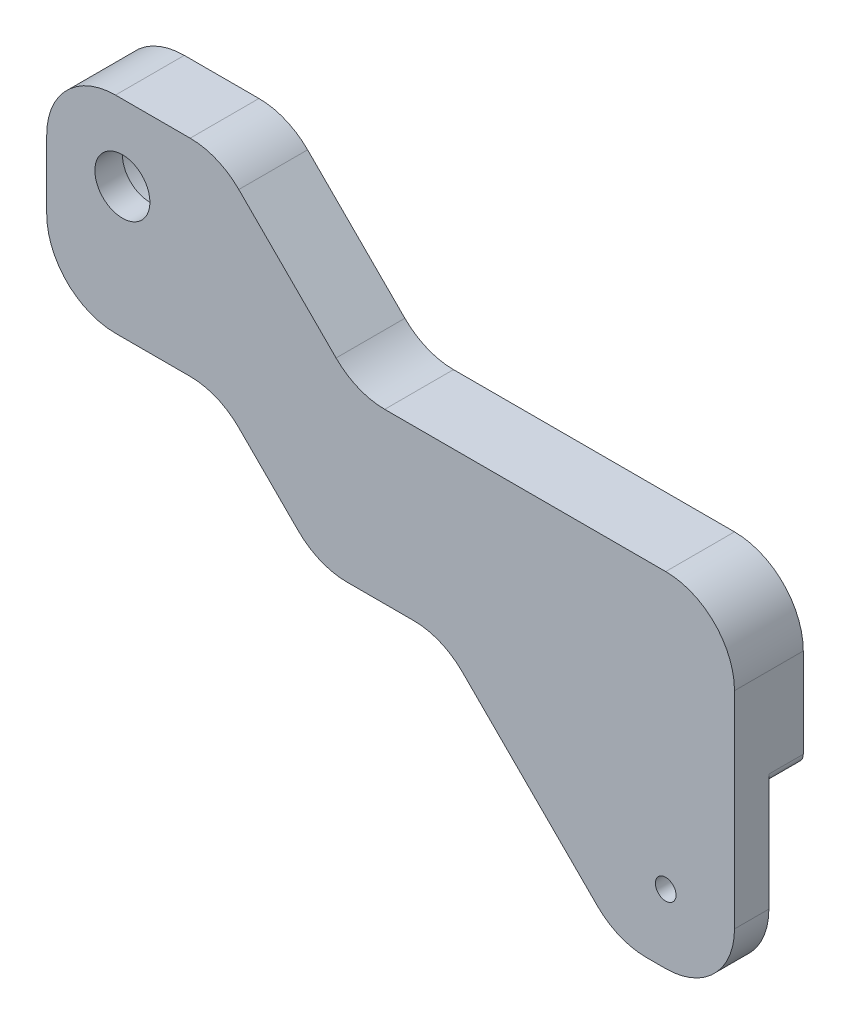
SolidWorks part; units mm, degrees
ref_plane "Plan de face" through (0, 0, 0) normal (0, 0, 1) x (1, 0, 0)
ref_plane "Plan de dessus" through (0, 0, 0) normal (0, 1, 0) x (1, 0, 0)
ref_plane "Plan de droite" through (0, 0, 0) normal (1, 0, 0) x (0, 0, -1)
sketch "Esquisse1" plane through (0, 0, 0) normal (0, 0, 1) x (1, 0, 0)
  line L1 (0, 0) -> (200, 0)
  line L2 (0, 0) -> (0, 100)
  line L3 (0, 100) -> (200, 100)
  line L4 (200, 0) -> (200, 100)
  dimension "D1" = 200
  dimension "D2" = 100
extrude "Boss.-Extru.1" add sketch "Esquisse1" along normal blind 20
sketch "Esquisse2" plane through (0, 0, 20) normal (0, 0, 1) x (1, 0, 0)
  line L0 (200, 20) -> (180, 20) construction
  line L1 (200, 0) -> (200, 100) construction
  line L2 (180, 20) -> (180, 0) construction
  line L3 (0, 0) -> (200, 0) construction
  circle A0 centre (180, 20) radius 3
  dimension "D3" = 6
  dimension "D1" = 20
  dimension "D2" = 20
extrude "Enlèv. mat.-Extru.1" cut sketch "Esquisse2" against normal through all both and the other way through all
sketch "Esquisse3" plane through (0, 0, 20) normal (0, 0, 1) x (1, 0, 0)
  line L0 (130, 0) -> (50, 80)
  line L1 (0, 0) -> (200, 0) construction
  line L2 (50, 80) -> (0, 80)
  line L3 (0, 100) -> (0, 0) construction
  line L4 (0, 80) -> (0, 0)
  line L5 (0, 0) -> (130, 0)
  dimension "D1" = 80
  dimension "D2" = 130
  dimension "D3" = 45
extrude "Enlèv. mat.-Extru.2" cut sketch "Esquisse3" against normal through all both and the other way through all
sketch "Esquisse4" plane through (0, 0, 0) normal (0, 0, -1) x (-1, 0, 0)
  line L0 (-130, 0) -> (-79, 51)
  line L2 (-130, 0) -> (-50, 80) construction
  line L3 (-79, 51) -> (-200, 51)
  line L4 (-200, 0) -> (-200, 100) construction
  line L5 (-200, 51) -> (-200, 0)
  line L6 (-200, 0) -> (-130, 0)
  dimension "D1" = 51
extrude "Enlèv. mat.-Extru.3" cut sketch "Esquisse4" against normal blind 10
sketch "Esquisse5" plane through (0, 0, 10) normal (0, 0, -1) x (-1, 0, 0)
  line L0 (-130, 0) -> (-166, 0)
  line L1 (-200, 0) -> (-130, 0) construction
  line L2 (-166, 0) -> (-115, 51)
  line L3 (-79, 51) -> (-200, 51) construction
  line L4 (-115, 51) -> (-79, 51)
  line L5 (-79, 51) -> (-130, 0)
  line L6 (-200, 51) -> (-200, 0) construction
  dimension "D1" = 34
  dimension "D2" = 45
extrude "Enlèv. mat.-Extru.4" cut sketch "Esquisse5" against normal through all both and the other way through all
sketch "Esquisse6" plane through (0, 0, 20) normal (0, 0, 1) x (1, 0, 0)
  line L0 (0, 100) -> (90, 100)
  line L1 (200, 100) -> (0, 100) construction
  line L2 (90, 100) -> (50, 140)
  line L3 (50, 140) -> (0, 140)
  line L4 (0, 140) -> (0, 100)
  dimension "D1" = 40
  dimension "D2" = 45
  dimension "D3" = 90
extrude "Boss.-Extru.2" add sketch "Esquisse6" against normal up to vertex (20 mm away)
sketch "Esquisse7" plane through (0, 0, 0) normal (0, 0, -1) x (-1, 0, 0)
  circle A0 centre (-22, 118) radius 17.5
  circle A1 centre (-180, 20) radius 3 construction
  dimension "D1" = 35
  dimension "D2" = 98
  dimension "D3" = 158
extrude "Enlèv. mat.-Extru.5" cut sketch "Esquisse7" against normal blind 11
sketch "Esquisse8" plane through (0, 0, 11) normal (0, 0, -1) x (-1, 0, 0)
  circle A0 centre (-22, 118) radius 8
  dimension "D1" = 16
extrude "Enlèv. mat.-Extru.6" cut sketch "Esquisse8" against normal through all both and the other way through all
sketch "Esquisse9" plane through (0, 0, 11) normal (0, 0, -1) x (-1, 0, 0)
  circle A0 centre (-22, 118) radius 14.5
  circle A1 centre (-22, 118) radius 17.5 construction
  dimension "D1" = 3
extrude "Enlèv. mat.-Extru.7" cut sketch "Esquisse9" against normal blind 1
fillet "Congé1" radius 20 10 edges at (200, 0, 15) (200, 100, 10) (90, 100, 10) (50, 140, 10) (0, 140, 10) (0, 80, 10) (50, 80, 10) (79, 51, 10) (115, 51, 15) (166, 0, 15)
fillet "Congé2" radius 3 1 edges at (200, 51, 5)
move or copy body "Corps-Déplacer/Copier1" [suppressed] bodies to move or copy 109
